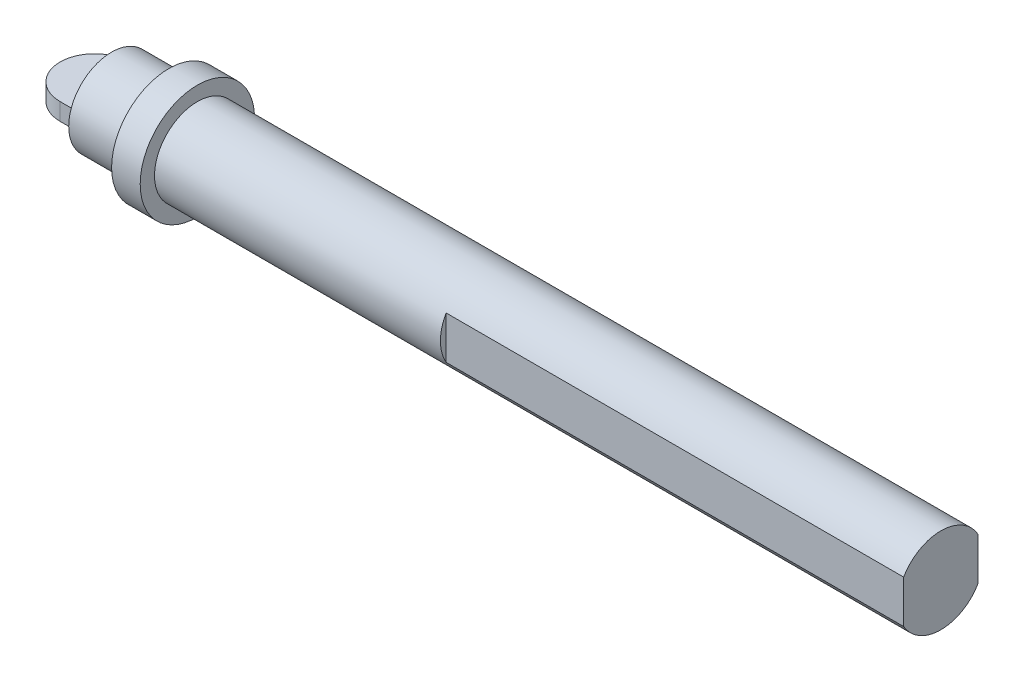
SolidWorks part; units mm, degrees
ref_plane "Front Plane" through (0, 0, 0) normal (0, 0, 1) x (1, 0, 0)
ref_plane "Top Plane" through (0, 0, 0) normal (0, 1, 0) x (1, 0, 0)
ref_plane "Right Plane" through (0, 0, 0) normal (1, 0, 0) x (0, 0, -1)
sketch "Sketch1" plane through (0, 0, 0) normal (0, 0, 1) x (1, 0, 0)
  line L0 (-72.8866, 0) -> (93.299, 0) construction
  line L1 (0, 0) -> (0, 7.5)
  line L2 (0, 7.5) -> (10, 7.5)
  line L3 (10, 7.5) -> (10, 10)
  line L4 (10, 10) -> (15, 10)
  line L5 (15, 10) -> (15, 7.5)
  line L6 (15, 7.5) -> (145, 7.5)
  line L7 (145, 7.5) -> (145, 0)
  line L8 (145, 0) -> (0, 0)
  dimension "D1" = 10
  dimension "D2" = 5
  dimension "D3" = 145
  dimension "D4" = 7.5
  dimension "D5" = 10
  dimension "D6" = 7.5
revolve "Revolve1" add sketch "Sketch1" angle 360 about L0
sketch "Sketch3" plane through (145, 0, 0) normal (1, 0, 0) x (0, 0, -1)
  line L0 (0, 11.194) -> (0, -12.2652) construction
  line L1 (-6.5, 3.7417) -> (-6.5, -3.7417)
  line L2 (6.5, 3.7417) -> (6.5, -3.7417)
  circle A0 centre (0, 0) radius 7.5 construction
  arc A1 (-6.5, -3.7417) -> (6.5, -3.7417) centre (0, 0) ccw
  arc A2 (6.5, 3.7417) -> (-6.5, 3.7417) centre (0, 0) ccw
  dimension "D1" = 6.5
extrude "Cut-Extrude1" cut sketch "Sketch3" against normal blind 80 flip side to cut contours A2 L1 A1 L2
sketch "Sketch4" plane through (0, 0, 0) normal (0, 1, 0) x (1, 0, 0)
  line L0 (-3, 6) -> (0, 6)
  line L1 (0, 7.5) -> (0, -7.5) construction
  line L2 (0, 6) -> (0, -6)
  line L3 (0, -6) -> (-3, -6)
  line L4 (0, 0) -> (-15.4612, 0) construction
  arc A0 (-3, 6) -> (-3, -6) centre (-3, 0) ccw
  dimension "D2" = 6
  dimension "D1" = 3
extrude "Boss-Extrude1" add sketch "Sketch4" along normal mid plane 3
